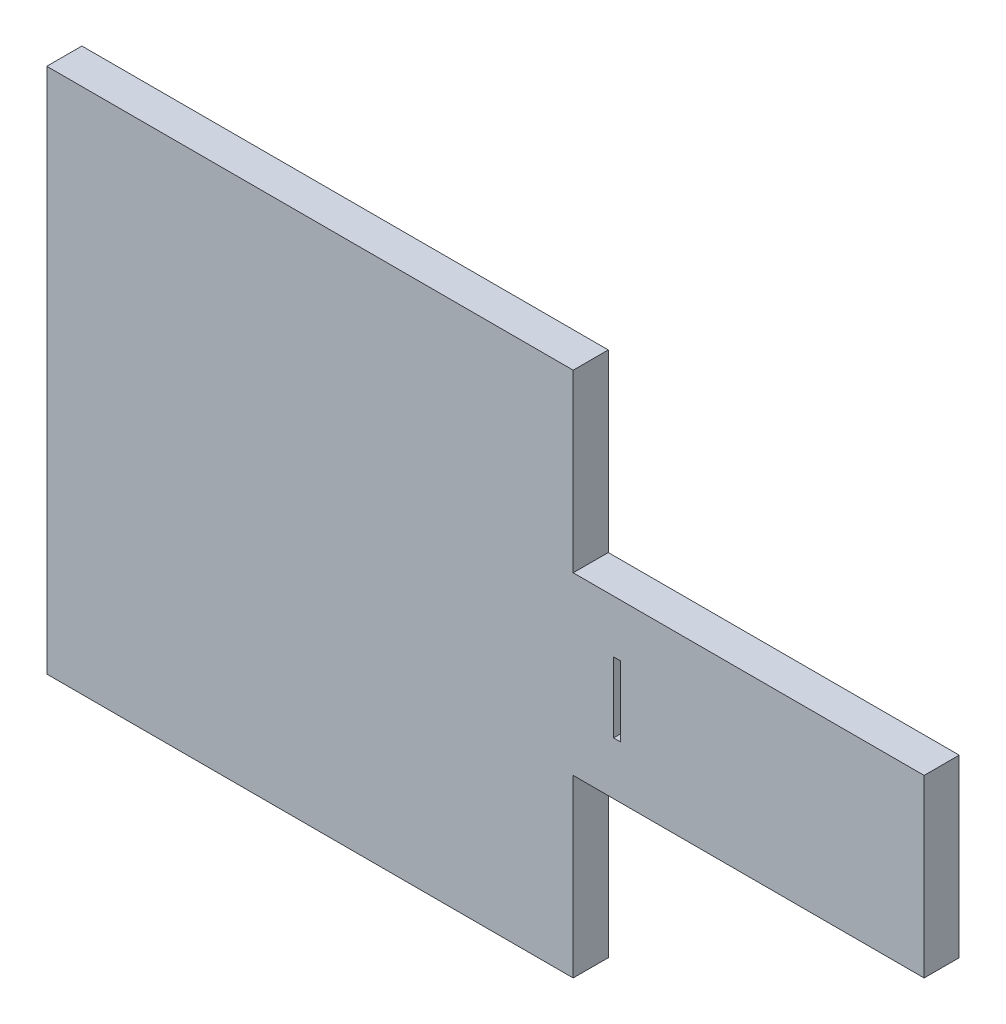
SolidWorks part; units mm, degrees
ref_plane "Front Plane" through (0, 0, 0) normal (0, 0, 1) x (1, 0, 0)
ref_plane "Top Plane" through (0, 0, 0) normal (0, 1, 0) x (1, 0, 0)
ref_plane "Right Plane" through (0, 0, 0) normal (1, 0, 0) x (0, 0, -1)
sketch "Sketch1" plane through (0, 0, 0) normal (0, 0, 1) x (1, 0, 0)
  line L2 (-6.35, 12.7) -> (-6.35, 25.4)
  line L3 (-6.35, 25.4) -> (-44.45, 25.4)
  line L5 (-44.45, -12.7) -> (-6.35, -12.7)
  line L6 (-6.35, -12.7) -> (-6.35, 0)
  line L8 (-3.175, 8.89) -> (-3.175, 3.81) construction
  line L9 (-44.45, -12.7) -> (-44.45, 25.4)
  line L10 (-3.429, 8.89) -> (-2.921, 8.89)
  line L11 (-3.429, 8.89) -> (-3.429, 3.81)
  line L12 (-3.429, 3.81) -> (-2.921, 3.81)
  line L13 (-2.921, 8.89) -> (-2.921, 3.81)
  line L14 (-3.429, 8.89) -> (-2.921, 3.81) construction
  line L15 (-3.429, 3.81) -> (-2.921, 8.89) construction
  line L16 (-6.35, 0) -> (19.05, 0)
  line L17 (19.05, 0) -> (19.05, 12.7)
  line L18 (19.05, 12.7) -> (-6.35, 12.7)
  point P11 (-3.175, 6.35)
  dimension "D1" = 25.4
  dimension "D2" = 38.1
  dimension "D3" = 12.7
  dimension "D4" = 12.7
  dimension "D6" = 0.508
  dimension "D7" = 5.08
  dimension "D9" = 38.1
extrude "Boss-Extrude1" add sketch "Sketch1" along normal blind 2.54
